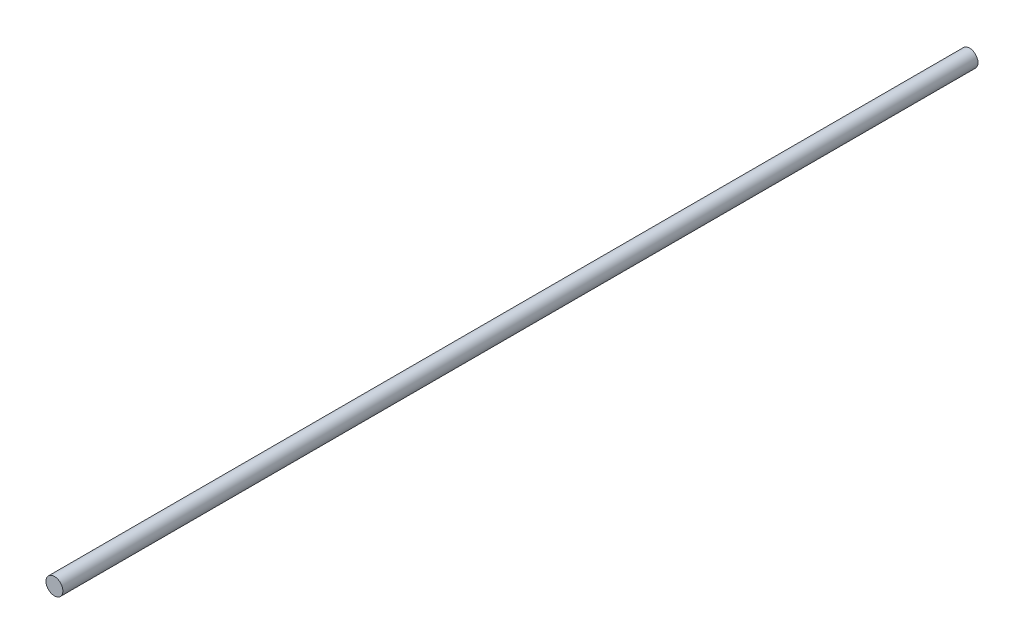
SolidWorks part; units mm, degrees
ref_plane "Front Plane" through (0, 0, 0) normal (0, 0, 1) x (1, 0, 0)
ref_plane "Top Plane" through (0, 0, 0) normal (0, 1, 0) x (1, 0, 0)
ref_plane "Right Plane" through (0, 0, 0) normal (1, 0, 0) x (0, 0, -1)
sketch "Sketch1" plane through (0, 0, 0) normal (0, 0, 1) x (1, 0, 0)
  line L0 (0, -2.4) -> (0, 2.4) construction
  circle A0 centre (0, 0) radius 2.4
  point P6 (0, 0)
  dimension "D1" = 4.8
  dimension "D2" = 4.8
extrude "Boss-Extrude1" add sketch "Sketch1" along normal blind 260
